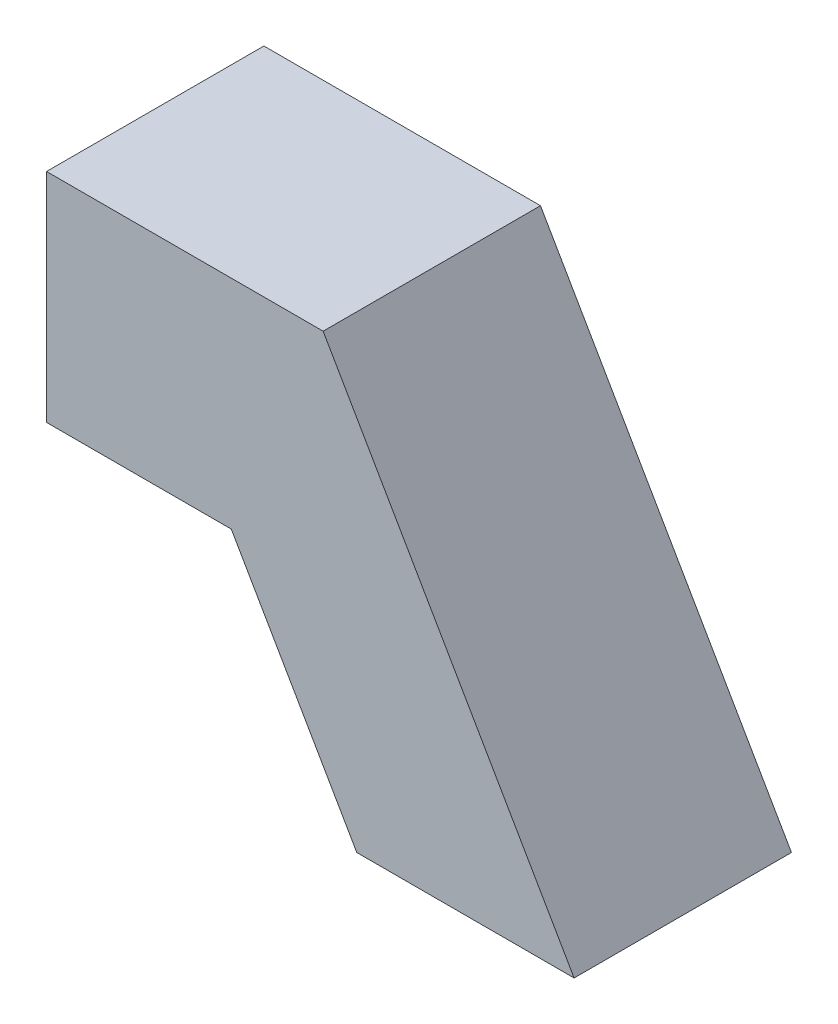
SolidWorks part; units mm, degrees
ref_plane "Front Plane" through (0, 0, 0) normal (0, 0, 1) x (1, 0, 0)
ref_plane "Top Plane" through (0, 0, 0) normal (0, 1, 0) x (1, 0, 0)
ref_plane "Right Plane" through (0, 0, 0) normal (1, 0, 0) x (0, 0, -1)
sketch "Sketch1" plane through (0, 0, 0) normal (0, 0, 1) x (1, 0, 0)
  line L0 (0, 0) -> (0, 20)
  line L1 (0, 20) -> (25.453, 20)
  line L2 (25.453, 20) -> (48.547, -20)
  line L3 (48.547, -20) -> (28.547, -20)
  line L4 (0, 0) -> (17, 0)
  line L5 (17, 0) -> (28.547, -20)
  dimension "D1" = 20
  dimension "D2" = 20
  dimension "D3" = 120
  dimension "D4" = 20
  dimension "D5" = 17
extrude "Boss-Extrude1" add sketch "Sketch1" along normal blind 20
